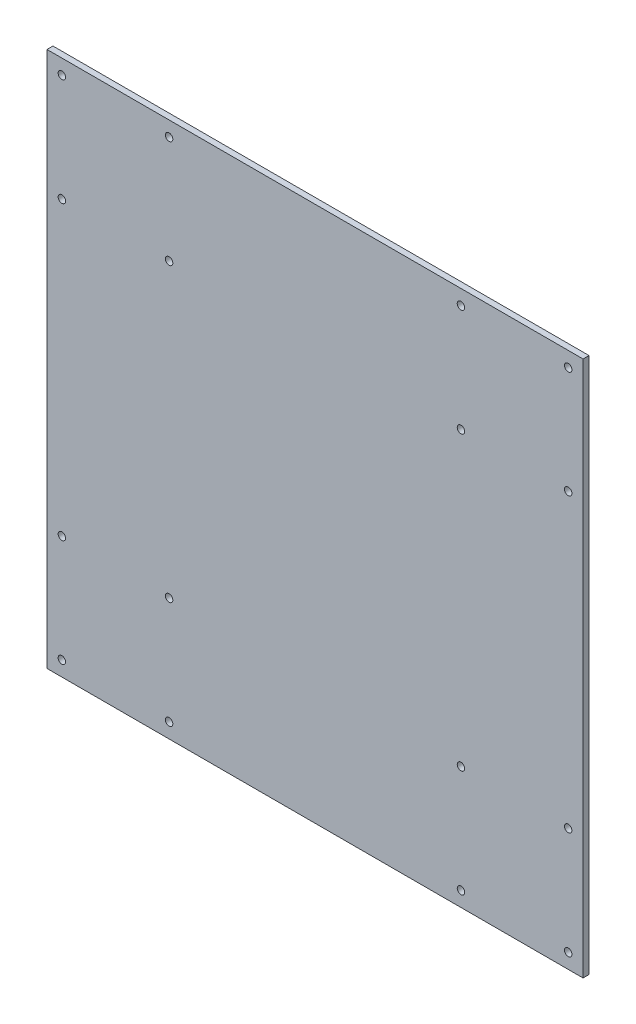
SolidWorks part; units mm, degrees
ref_plane "正面" through (0, 0, 0) normal (0, 0, 1) x (1, 0, 0)
ref_plane "平面" through (0, 0, 0) normal (0, 1, 0) x (1, 0, 0)
ref_plane "右側面" through (0, 0, 0) normal (1, 0, 0) x (0, 0, -1)
sketch "ｽｹｯﾁ1" plane through (0, 0, 0) normal (0, 0, 1) x (1, 0, 0)
  line L1 (0, 0) -> (180, 0)
  line L2 (0, 0) -> (0, 180)
  line L3 (0, 180) -> (180, 180)
  line L4 (180, 0) -> (180, 180)
  dimension "D1" = 180
  dimension "D2" = 180
extrude "ﾎﾞｽ - 押し出し1" add sketch "ｽｹｯﾁ1" along normal blind 2
hole_wizard "M3x0.5 ねじ穴1" positions "ｽｹｯﾁ4" profile "ｽｹｯﾁ5" tap size "M3x0.5" standard "JIS" end condition through all
sketch "ｽｹｯﾁ4" plane through (0, 0, 2) normal (0, 0, 1) x (1, 0, 0)
  line L0 (180, 0) -> (180, 180) construction
  line L1 (0, 0) -> (180, 0) construction
  point P0 (175, 5)
  point P2 (175, 41)
  point P4 (139, 41)
  point P6 (139, 5)
  dimension "D1" = 36
  dimension "D2" = 5
  dimension "D3" = 5
  dimension "D4" = 36
  dimension "D5" = 36
  dimension "D6" = 36
  dimension "D7" = 5
sketch "ｽｹｯﾁ5" plane through (175, 5, 2) normal (1, 0, 0) x (0, -1, 0)
  line L0 (0, 0) -> (0, 2)
  line L1 (0, 2) -> (1.25, 2)
  line L2 (1.25, 2) -> (1.25, 0)
  line L5 (1.25, 0) -> (0, 0)
  line L11 (0, -6.35) -> (0, 107.95) construction
  dimension "次ｻｰﾌｪｽまでのねじ下穴ﾄﾞﾘﾙ直径" = 2.5
  dimension "次ｻｰﾌｪｽまでのねじ下穴ﾄﾞﾘﾙの深さ" = 2
cosmetic thread "穴のねじ山1" parameters "D2"=3
cosmetic thread "穴のねじ山2" parameters "D2"=3
cosmetic thread "穴のねじ山3" parameters "D2"=3
cosmetic thread "穴のねじ山4" parameters "D2"=3
ref_plane "平面1" through (90, 0, 0) normal (1, 0, 0) x (0, 0, -1)
ref_plane "平面2" through (0, 90, 0) normal (0, 1, 0) x (1, 0, 0)
mirror "ﾐﾗｰ1" about plane through (0, 90, 0) normal (0, 1, 0) of "M3x0.5 ねじ穴1"
mirror "ﾐﾗｰ2" about plane through (90, 0, 0) normal (1, 0, 0) of "ﾐﾗｰ1", "M3x0.5 ねじ穴1"
